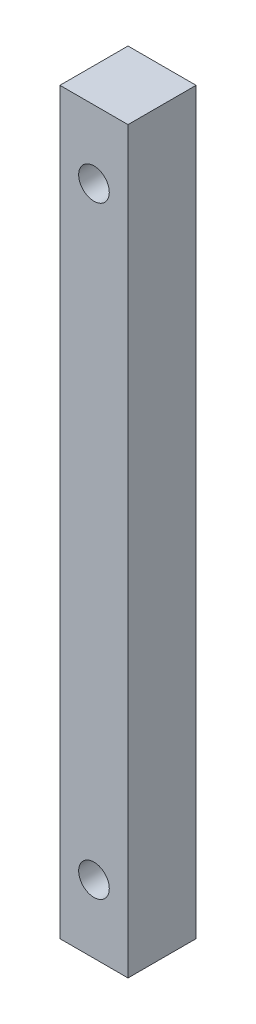
SolidWorks part; units mm, degrees
material "7075-T6, Plate (SS)"
ref_plane "Front Plane" through (0, 0, 0) normal (0, 0, 1) x (1, 0, 0)
ref_plane "Top Plane" through (0, 0, 0) normal (0, 1, 0) x (1, 0, 0)
ref_plane "Right Plane" through (0, 0, 0) normal (1, 0, 0) x (0, 0, -1)
sketch "Sketch1" plane through (0, 0, 0) normal (0, 0, 1) x (1, 0, 0)
  line L0 (-2.54, 39.4449) -> (-2.54, -15.7151) construction
  line L2 (-5.08, 39.4449) -> (0, 39.4449)
  line L3 (-5.08, 39.4449) -> (-5.08, -15.7151)
  line L4 (-5.08, -15.7151) -> (0, -15.7151)
  line L5 (0, 39.4449) -> (0, -15.7151)
  circle A0 centre (-2.54, 34.3649) radius 1.143
  circle A1 centre (-2.54, -10.6351) radius 1.143
  dimension "D1" = 2.286
  dimension "D3" = 2.286
  dimension "D4" = 5.08
  dimension "D5" = 5.08
  dimension "D6" = 45
  dimension "D2" = 5.08
extrude "Boss-Extrude1" add sketch "Sketch1" along normal blind 5.08
